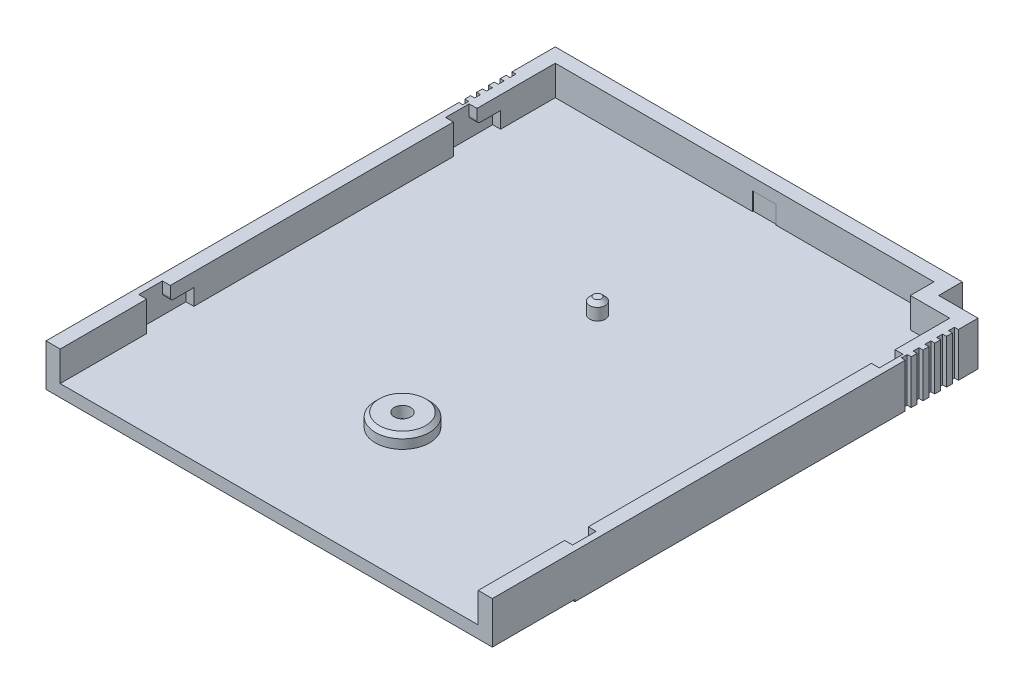
SolidWorks part; units mm, degrees
ref_plane "Front Plane" through (0, 0, 0) normal (0, 0, 1) x (1, 0, 0)
ref_plane "Top Plane" through (0, 0, 0) normal (0, 1, 0) x (1, 0, 0)
ref_plane "Right Plane" through (0, 0, 0) normal (1, 0, 0) x (0, 0, -1)
sketch "Sketch1" plane through (0, 0, 0) normal (0, 1, 0) x (1, 0, 0)
  line L0 (0, -32.375) -> (0, 32.375) construction
  line L1 (23.375, 32.375) -> (-28.375, 32.375)
  line L2 (28.375, 29.375) -> (28.375, -32.375)
  line L3 (28.375, -32.375) -> (-28.375, -32.375)
  line L4 (-28.375, 32.375) -> (-28.375, -32.375)
  line L5 (28.375, 32.375) -> (-28.375, -32.375) construction
  line L6 (28.375, -32.375) -> (-28.375, 32.375) construction
  line L9 (28.375, 29.375) -> (23.375, 29.375)
  line L10 (23.375, 32.375) -> (23.375, 29.375)
  point P0 (0, 0)
  dimension "D1" = 56.75
  dimension "D2" = 64.75
  dimension "D3" = 3
  dimension "D4" = 5
extrude "Boss-Extrude1" add sketch "Sketch1" along normal blind 5.6
shell "Shell1" thickness 1.8
sketch "Sketch2" plane through (0, 0, 32.375) normal (0, 0, 1) x (1, 0, 0)
  line L0 (-28.375, 5.6) -> (28.375, 5.6) construction
  line L1 (-26.575, 5.6) -> (26.575, 5.6)
  line L2 (-26.575, 5.6) -> (-26.575, 1.8)
  line L3 (-26.575, 1.8) -> (26.575, 1.8)
  line L4 (26.575, 5.6) -> (26.575, 1.8)
  line L5 (-26.575, 5.6) -> (-26.575, 1.8) construction
  line L6 (26.575, 5.6) -> (26.575, 1.8) construction
  line L7 (-26.575, 1.8) -> (26.575, 1.8) construction
extrude "Cut-Extrude1" cut sketch "Sketch2" against normal up to next
sketch "Sketch3" plane through (0, 0, 0) normal (0, -1, 0) x (1, 0, 0)
  line L1 (-27.875, -26.125) -> (-28.375, -26.125)
  line L2 (-27.875, -26.125) -> (-27.875, -26.875)
  line L3 (-27.875, -26.875) -> (-28.375, -26.875)
  line L4 (-28.375, -26.125) -> (-28.375, -26.875)
  line L7 (-28.375, -32.375) -> (-28.375, 32.375) construction
  line L8 (23.375, -32.375) -> (-28.375, -32.375) construction
  line L9 (0, 32.375) -> (0, -32.375) construction
  line L10 (0, 32.375) -> (0, -32.375) construction
  line L11 (28.375, -26.125) -> (28.375, -26.875)
  line L12 (27.875, -26.875) -> (28.375, -26.875)
  line L13 (27.875, -26.125) -> (27.875, -26.875)
  line L14 (27.875, -26.125) -> (28.375, -26.125)
  dimension "D1" = 0.5
  dimension "D2" = 0.75
  dimension "D3" = 5.5
extrude "Cut-Extrude2" cut sketch "Sketch3" against normal blind 5.6
pattern_linear "LPattern1" count 5 spacing 1.5 along (0, 0, 1) of "Cut-Extrude2"
sketch "Sketch4" plane through (0, 1.8, 0) normal (0, 1, 0) x (1, 0, 0)
  line L0 (0, -32.375) -> (0, 30.575) construction
  line L1 (-26.575, -32.375) -> (26.575, -32.375) construction
  line L2 (21.575, 30.575) -> (-26.575, 30.575) construction
  circle A0 centre (0, -15.425) radius 1.05
  circle A1 centre (0, -15.425) radius 3.45
  dimension "D1" = 2.1
  dimension "D2" = 6.9
  dimension "D3" = 13.5
extrude "Boss-Extrude2" add sketch "Sketch4" along normal blind 1.66
sketch "Sketch5" plane through (0, 1.8, 0) normal (0, 1, 0) x (1, 0, 0)
  line L0 (0, -32.375) -> (0, 30.575) construction
  line L1 (-26.575, -32.375) -> (26.575, -32.375) construction
  line L2 (21.575, 30.575) -> (-26.575, 30.575) construction
  line L3 (21.575, 30.575) -> (-26.575, 30.575) construction
  circle A0 centre (0, 9.375) radius 1
  dimension "D1" = 2
  dimension "D2" = 20.2
extrude "Boss-Extrude3" add sketch "Sketch5" along normal blind 2
chamfer "Chamfer1" distance 0.5 angle 45 2 edges at (0, 3.46, 18.875) (0, 3.8, -8.375)
sketch "Sketch6" plane through (0, 0, 0) normal (0, -1, 0) x (1, 0, 0)
  line L0 (0, 32.375) -> (0, -32.375) construction
  line L1 (-28.375, 32.375) -> (28.375, 32.375) construction
  line L2 (23.375, -32.375) -> (-28.375, -32.375) construction
  circle A1 centre (0, 15.425) radius 2.5
  point P8 (0, 14.925)
  point P11 (0, 15.425)
  dimension "D1" = 5
extrude "Cut-Extrude3" cut sketch "Sketch6" against normal blind 2
sketch "Sketch7" plane through (26.575, 0, 0) normal (-1, 0, 0) x (0, 0, 1)
  line L0 (32.375, 1.8) -> (-27.575, 1.8) construction
  line L1 (15.375, 1.8) -> (21.375, 1.8)
  line L2 (15.375, 1.8) -> (15.375, 3.8661)
  line L3 (15.375, 3.8661) -> (17.975, 3.8661)
  line L4 (21.375, 1.8) -> (21.375, 5.6)
  line L5 (32.375, 5.6) -> (-27.575, 5.6) construction
  line L7 (21.375, 1.8) -> (21.375, 5.6)
  line L8 (21.375, 5.6) -> (18.375, 5.6)
  line L9 (18.375, 4.2661) -> (18.375, 5.6)
  line L10 (32.375, 1.8) -> (32.375, 5.6) construction
  arc A0 (17.975, 3.8661) -> (18.375, 4.2661) centre (17.975, 4.2661) ccw
  line M9 (-27.575, 1.8) -> (32.375, 1.8)
  line M11 (32.375, 5.6) -> (-27.575, 5.6)
  dimension "D1" = 0.4
  dimension "D2" = 11
  dimension "D3" = 3
  dimension "D4" = 2.0661
  dimension "D5" = 6
extrude "Cut-Extrude4" cut sketch "Sketch7" against normal blind 1 contours A0 L3 L2 L4 L9 M9 M11
pattern_linear "LPattern2" count 2 spacing 39 along (0, 0, -1) of "Cut-Extrude4"
mirror "Mirror1" about plane through (0, 0, 0) normal (1, 0, 0) of "LPattern2", "Cut-Extrude4"
sketch "Sketch8" plane through (0, 0, 0) normal (0, -1, 0) x (1, 0, 0)
  line L0 (28.375, 32.375) -> (28.375, -20.125) construction
  line L1 (-28.375, 32.375) -> (28.375, 32.375)
  line L2 (-28.375, 32.375) -> (-28.375, 21.875)
  line L3 (-28.375, 21.875) -> (28.375, 21.875)
  line L4 (28.375, 32.375) -> (28.375, 21.875)
  dimension "D1" = 10.5
extrude "Cut-Extrude5" cut sketch "Sketch8" against normal blind 0.25
sketch "Sketch9" plane through (0, 0, 0) normal (0, -1, 0) x (1, 0, 0)
  line L0 (-28.375, 21.875) -> (28.375, 21.875) construction
  line L1 (13.375, 21.875) -> (16.375, 21.875)
  line L2 (13.375, 21.875) -> (13.375, -32.375)
  line L3 (13.375, -32.375) -> (16.375, -32.375)
  line L4 (16.375, 21.875) -> (16.375, -32.375)
  line L5 (23.375, -32.375) -> (-28.375, -32.375) construction
  line L6 (28.375, 21.875) -> (28.375, -20.125) construction
  dimension "D1" = 3
  dimension "D2" = 12
extrude "Cut-Extrude6" cut sketch "Sketch9" against normal blind 0.1
mirror "Mirror2" about plane through (0, 0, 0) normal (1, 0, 0) of "Cut-Extrude6"
sketch "Sketch10" plane through (0, 0, 0) normal (0, -1, 0) x (1, 0, 0)
  line L0 (13.375, -32.375) -> (-13.375, -32.375) construction
  line L1 (10, -27.375) -> (-10, -27.375)
  line L2 (10, -27.375) -> (10, -30.375)
  line L3 (10, -30.375) -> (-10, -30.375)
  line L4 (-10, -27.375) -> (-10, -30.375)
  line L5 (10, -27.375) -> (-10, -30.375) construction
  line L6 (10, -30.375) -> (-10, -27.375) construction
  point P0 (0, -28.875)
  dimension "D1" = 20
  dimension "D2" = 2
  dimension "D3" = 3
extrude "Cut-Extrude7" cut sketch "Sketch10" against normal blind 0.1
sketch "Sketch11" plane through (0, 0, -30.575) normal (0, 0, 1) x (1, 0, 0)
  line L0 (0, 0) -> (0, 5.6) construction
  line L1 (21.575, 5.6) -> (-26.575, 5.6) construction
  line L2 (21.575, 1.8) -> (-26.575, 1.8) construction
  line L3 (1.5, 4.1) -> (-1.5, 4.1)
  line L4 (1.5, 4.1) -> (1.5, 1.8)
  line L5 (1.5, 1.8) -> (-1.5, 1.8)
  line L6 (-1.5, 4.1) -> (-1.5, 1.8)
  line L7 (1.5, 4.1) -> (-1.5, 1.8) construction
  line L8 (1.5, 1.8) -> (-1.5, 4.1) construction
  point P5 (0, 2.95)
  dimension "D1" = 3
  dimension "D2" = 1.5
extrude "Cut-Extrude8" cut sketch "Sketch11" against normal blind 0.1
